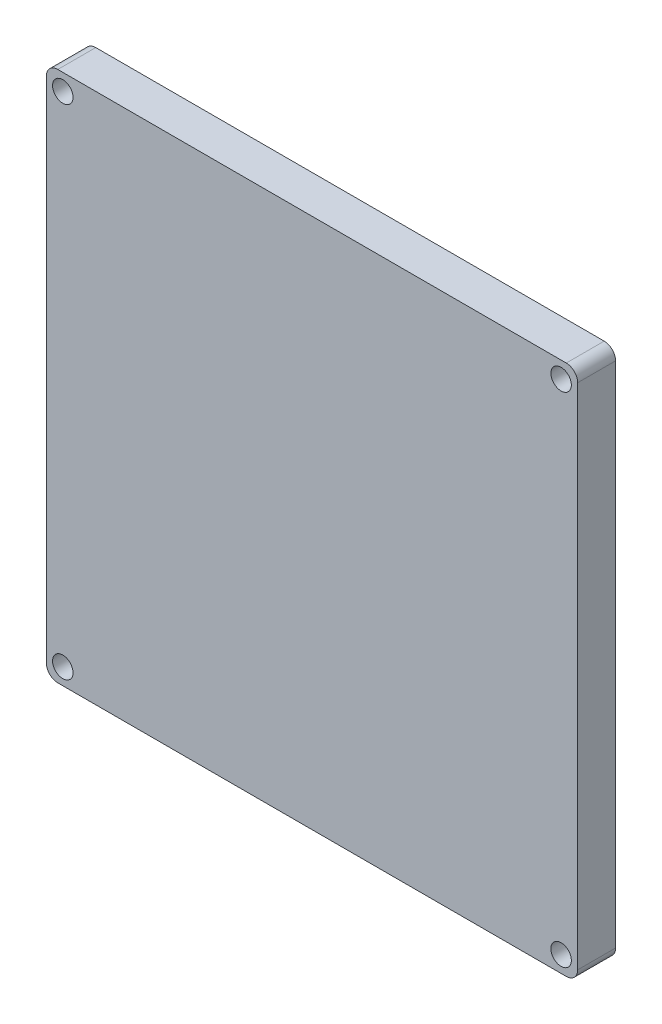
SolidWorks part; units mm, degrees
ref_plane "Front Plane" through (0, 0, 0) normal (0, 0, 1) x (1, 0, 0)
ref_plane "Top Plane" through (0, 0, 0) normal (0, 1, 0) x (1, 0, 0)
ref_plane "Right Plane" through (0, 0, 0) normal (1, 0, 0) x (0, 0, -1)
sketch "Sketch1" plane through (0, 0, 0) normal (0, 0, 1) x (1, 0, 0)
  line L1 (-35, 35) -> (35, 35)
  line L2 (-35, 35) -> (-35, -35)
  line L3 (-35, -35) -> (35, -35)
  line L4 (35, 35) -> (35, -35)
  line L5 (-35, 35) -> (35, -35) construction
  line L6 (-35, -35) -> (35, 35) construction
  circle A0 centre (-32.84, 32.82) radius 1.35
  circle A2 centre (-32.84, -32.84) radius 1.35
  circle A3 centre (32.82, -32.84) radius 1.35
  circle A4 centre (32.82, 32.82) radius 1.35
  point P0 (0, 0)
  dimension "D5" = 2.7
  dimension "D7" = 2.7
  dimension "D9" = 2.7
  dimension "D12" = 2.7
  dimension "D1" = 70
  dimension "D2" = 70
  dimension "D3" = 2.16
  dimension "D4" = 2.16
  dimension "D6" = 65.66
  dimension "D8" = 65.66
  dimension "D10" = 65.66
  dimension "D11" = 65.66
extrude "Boss-Extrude1" add sketch "Sketch1" along normal blind 5
fillet "Fillet1" radius 1.5 4 edges at (35, 35, 2.5) (35, -35, 2.5) (-35, -35, 2.5) (-35, 35, 2.5)
sketch "Sketch2" plane through (0, 0, 0) normal (0, 0, -1) x (-1, 0, 0)
  line L0 (0, 0) -> (0, -35) construction
  line L1 (33.5, -35) -> (-33.5, -35) construction
  line L2 (0, 0) -> (-35, 0) construction
  line L3 (-35, -33.5) -> (-35, 33.5) construction
  line L5 (13.3791, -35) -> (-10.9806, -35)
  line L6 (13.3791, -35) -> (13.3791, -15.3937)
  line L7 (13.3791, -15.3937) -> (-10.9806, -15.3937)
  line L8 (-10.9806, -35) -> (-10.9806, -15.3937)
extrude "Boss-Extrude2" add sketch "Sketch2" along normal blind 9
